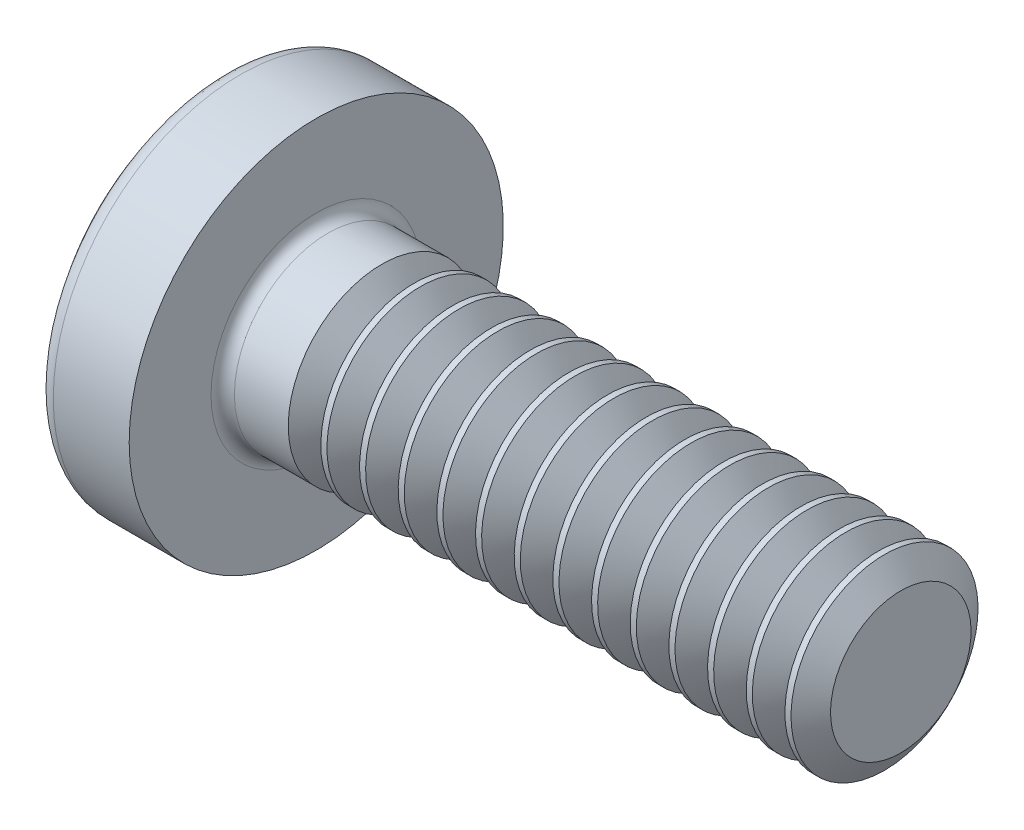
SolidWorks part; units mm, degrees
ref_plane "Plane1" through (0, 0, 0) normal (0, 0, 1) x (1, 0, 0)
ref_plane "Plane2" through (0, 0, 0) normal (0, 1, 0) x (1, 0, 0)
ref_plane "Plane3" through (0, 0, 0) normal (1, 0, 0) x (0, 0, -1)
sketch "BodySke" plane through (0, 0, 0) normal (0, 0, 1) x (1, 0, 0)
  line L0 (1.3, 0.8) -> (1.3, 1.6)
  line L1 (1.475, 6.35) -> (1.475, -3.175) construction
  line L2 (-25.4, 0) -> (127, 0) construction
  line L3 (6.3, 0) -> (0, 0)
  line L4 (1.3, 0.8) -> (6.3, 0.8)
  line L5 (6.3, 0.8) -> (6.3, 0)
  line L6 (0.6507, 1.6) -> (1.3, 1.6)
  line L8 (1.3, 6.35) -> (1.3, -3.175) construction
  arc A0 (0.5326, 1.5426) -> (0, 0) centre (2.5, 0) ccw
  arc A2 (0.5326, 1.5426) -> (0.6507, 1.6) centre (0.6507, 1.45) cw
  dimension "Head_crown_rad" = 2.5
  dimension "Head_fillet_rad" = 0.15
  dimension "Length" = 5
  dimension "Head_ht" = 1.3
  dimension "Head_dia" = 3.2
  dimension "Advance" = 0.35
  dimension "Thread_nom" = 5
  dimension "Diameter" = 1.6
revolve "Base-Revolve" add sketch "BodySke"
cosmetic thread "ThreadCosmetic" [suppressed]
fillet "Fillet1" radius 0.1 1 edges at (1.3, 0, 0.8)
sketch "Sketch3" plane through (0, 0, 0) normal (1, 0, 0) x (0, 0, -1)
  line L0 (0.24, -0.8) -> (-0.24, -0.8)
  line L1 (0.24, -0.8) -> (0.24, 0.8)
  line L2 (-0.24, 0.8) -> (0.24, 0.8)
  line L3 (-0.24, 0.8) -> (-0.24, -0.8)
  dimension "Cross_dia" = 1.6
  dimension "D1" = 0.8
  dimension "Cross_width" = 0.48
  dimension "D2" = 0.24
ref_plane "Plane4" through (0.9, 0, 0) normal (1, 0, 0) x (0, 0, -1)
sketch "Sketch4" plane through (0.9, 0, 0) normal (1, 0, 0) x (0, 0, -1)
  line L0 (0.24, -0.3513) -> (-0.24, -0.3513)
  line L1 (0.24, -0.3513) -> (0.24, 0.3513)
  line L2 (-0.24, 0.3513) -> (0.24, 0.3513)
  line L3 (-0.24, 0.3513) -> (-0.24, -0.3513)
  dimension "D1" = 0.48
  dimension "D2" = 0.7026
  dimension "D3" = 0.24
  dimension "D4" = 0.3513
loft "Recess" cut profiles "Sketch3", "Sketch4"
pattern_circular "RecPat" count 2 every 90 about axis through (0, 0, 0) along (1, 0, 0) of "Recess"
sketch "RecCorSke" plane through (0, 0, 0) normal (0, 0, 1) x (1, 0, 0)
  line L0 (-3.175, 0) -> (15.875, 0) construction
  line L1 (-25.4, 0) -> (127, 0) construction
  line L2 (0, 0) -> (0, 0.4184)
  line L3 (0, 0.4184) -> (0.9, 0.3555)
  line L4 (0.9, 0.3555) -> (1.0155, 0)
  line L5 (1.0155, 0) -> (0, 0)
  dimension "Diameter" = 0.711
  dimension "Depth" = 0.9
  dimension "Draft_angle" = 4
  dimension "Bottom_angle" = 18
revolve "RecessCore" cut sketch "RecCorSke" angle 360 about L0
sketch "ThdSchSke" plane through (0, 0, 0) normal (0, 0, 1) x (1, 0, 0)
  line L0 (2, -0.601) -> (1.8607, -0.8)
  line L1 (2, -0.601) -> (2.1393, -0.8)
  line L2 (2.1393, -0.8) -> (2.1393, -1)
  line L3 (-3.175, 0) -> (5.1513, 0) construction
  line L5 (2.1393, -1) -> (1.8607, -1)
  line L6 (1.8607, -1) -> (1.8607, -0.8)
  dimension "Diameter" = 1.6
  dimension "SideAngle" = 55
  dimension "VeeAngle" = 70
  dimension "Thread_minor" = 1.202
  dimension "Overcut" = 2
  dimension "Start" = 2
revolve "ThreadSchematic" cut sketch "ThdSchSke" angle 360 about L3
pattern_linear "ThdSchPat" count 14 spacing 0.3308 along (1, 0, 0) of "ThreadSchematic"
equation "\"D1@Sketch3\" = \"Cross_dia@Sketch3\" / 2"
equation "\"D2@Sketch3\" = \"Cross_width@Sketch3\" / 2"
equation "\"Depth@RecCorSke\" = \"Cross_depth@Plane4\""
equation "\"D1@Sketch4\" = \"Cross_width@Sketch3\""
equation "\"D2@Sketch4\" = \"Cross_dia@Sketch3\" - 2.0 * \"Cross_depth@Plane4\" * tan(26.5  * 0.017453292)"
equation "\"D3@Sketch4\" = \"D1@Sketch4\" / 2"
equation "\"D4@Sketch4\" = \"D2@Sketch4\" / 2"
equation "\"Thread_length@ThreadCosmetic\" = ((sgn( (\"Length@BodySke\" - \"Advance@BodySke\" * 2.0 ) - \"Thread_nom@BodySke\" )-1)*( (\"Length@BodySke\" - \"Advance@BodySke\" * 2.0 ) - \"Thread_nom@BodySke\" ))/-2+ \"Thread_nom@BodySke\""
equation "\"Thread_minor@ThdSchSke\" = \"Thread_minor@ThreadCosmetic\""
equation "\"Diameter@ThdSchSke\" = \"Diameter@BodySke\""
equation "\"Overcut@ThdSchSke\" = \"Diameter@BodySke\" * 1.25"
equation "\"Start@ThdSchSke\" = \"Head_ht@BodySke\" + \"Length@BodySke\" - \"Thread_length@ThreadCosmetic\"  '---Non-countersunk---"
equation "\"Num_threads@ThdSchPat\" = int( \"Thread_length@ThreadCosmetic\" / \"Advance@BodySke\" + 0.999 )  + 1"
equation "\"Advance@ThdSchPat\" = \"Thread_length@ThreadCosmetic\" /  (\"Num_threads@ThdSchPat\" - 1) 'relax it"
